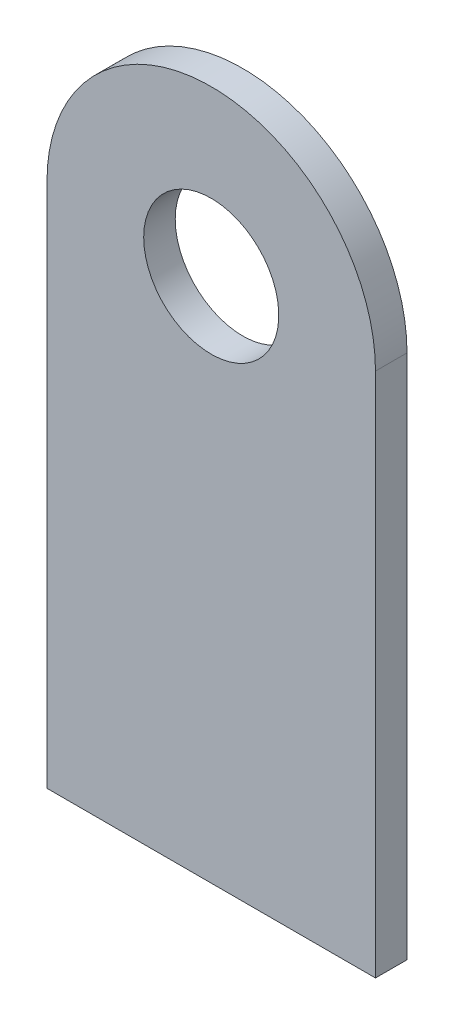
SolidWorks part; units mm, degrees
ref_plane "Front Plane" through (0, 0, 0) normal (0, 0, 1) x (1, 0, 0)
ref_plane "Top Plane" through (0, 0, 0) normal (0, 1, 0) x (1, 0, 0)
ref_plane "Right Plane" through (0, 0, 0) normal (1, 0, 0) x (0, 0, -1)
sketch "Sketch1" plane through (0, 0, 0) normal (0, 0, 1) x (1, 0, 0)
  line L0 (0, 0) -> (0, 25.4)
  line L1 (15.875, 25.4) -> (15.875, 0)
  line L2 (15.875, 0) -> (0, 0)
  arc A0 (0, 25.4) -> (15.875, 25.4) centre (7.9375, 25.4) cw
  circle A1 centre (7.9375, 25.4) radius 3.2639
  dimension "D2" = 6.5278
  dimension "D1" = 25.4
  dimension "D3" = 15.875
extrude "Boss-Extrude1" add sketch "Sketch1" along normal blind 1.524
